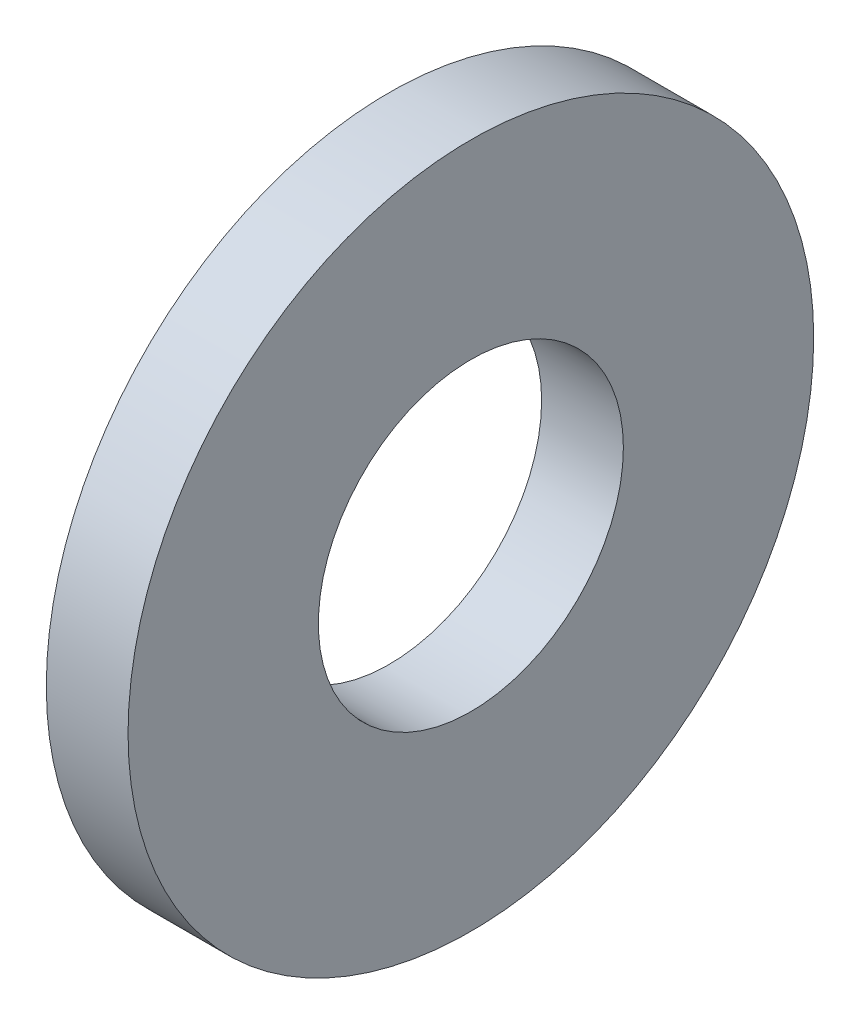
SolidWorks part; units mm, degrees
ref_plane "Front Plane" through (0, 0, 0) normal (0, 0, 1) x (1, 0, 0)
ref_plane "Top Plane" through (0, 0, 0) normal (0, 1, 0) x (1, 0, 0)
ref_plane "Right Plane" through (0, 0, 0) normal (1, 0, 0) x (0, 0, -1)
sketch "Sketch1" plane through (0, 0, 0) normal (1, 0, 0) x (0, 0, -1)
  circle A0 centre (0, 0) radius 3.175
  circle A1 centre (0, 0) radius 7.1374
  dimension "OD" = 6.35
  dimension "ID" = 14.2748
extrude "Boss-Extrude1" add sketch "Sketch1" along normal blind 1.7018
